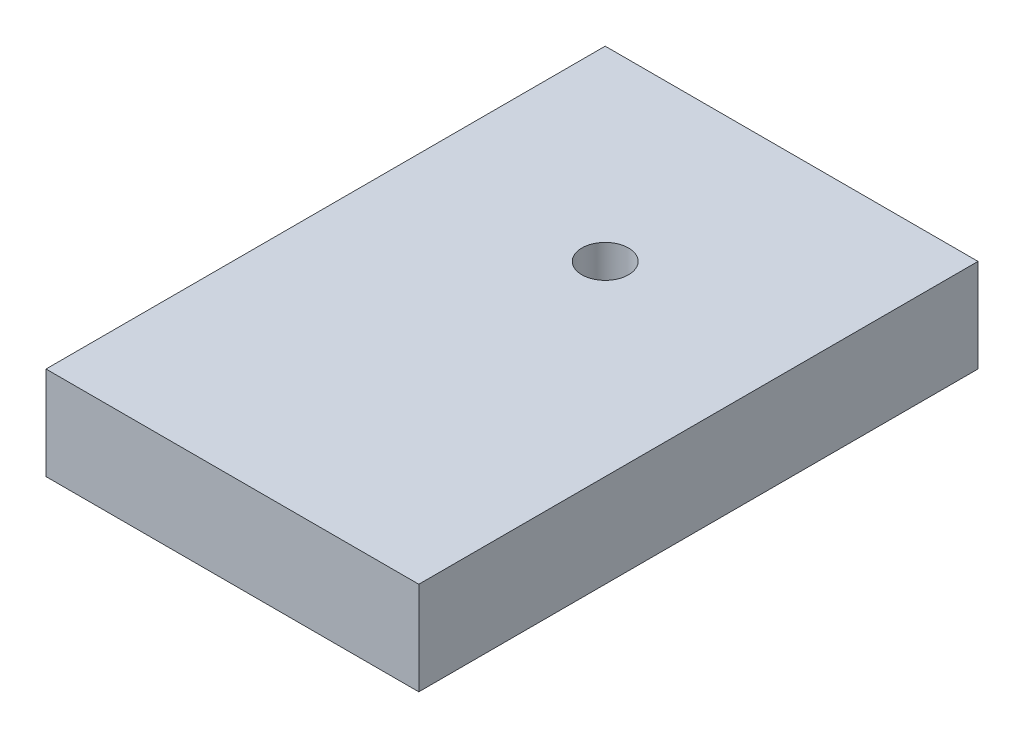
SolidWorks part; units mm, degrees
ref_plane "Front Plane" through (0, 0, 0) normal (0, 0, 1) x (1, 0, 0)
ref_plane "Top Plane" through (0, 0, 0) normal (0, 1, 0) x (1, 0, 0)
ref_plane "Right Plane" through (0, 0, 0) normal (1, 0, 0) x (0, 0, -1)
sketch "Sketch1" plane through (0, 0, 0) normal (0, 1, 0) x (1, 0, 0)
  line L0 (12.7, 0) -> (12.7, -38.1) construction
  line L1 (0, 0) -> (25.4, 0)
  line L2 (0, 0) -> (0, -38.1)
  line L3 (0, -38.1) -> (25.4, -38.1)
  line L4 (25.4, 0) -> (25.4, -38.1)
  circle A0 centre (12.7, -12.7) radius 1.5875
  dimension "D3" = 3.175
  dimension "D1" = 25.4
  dimension "D2" = 38.1
  dimension "D4" = 12.7
extrude "Boss-Extrude1" add sketch "Sketch1" along normal blind 6.35
